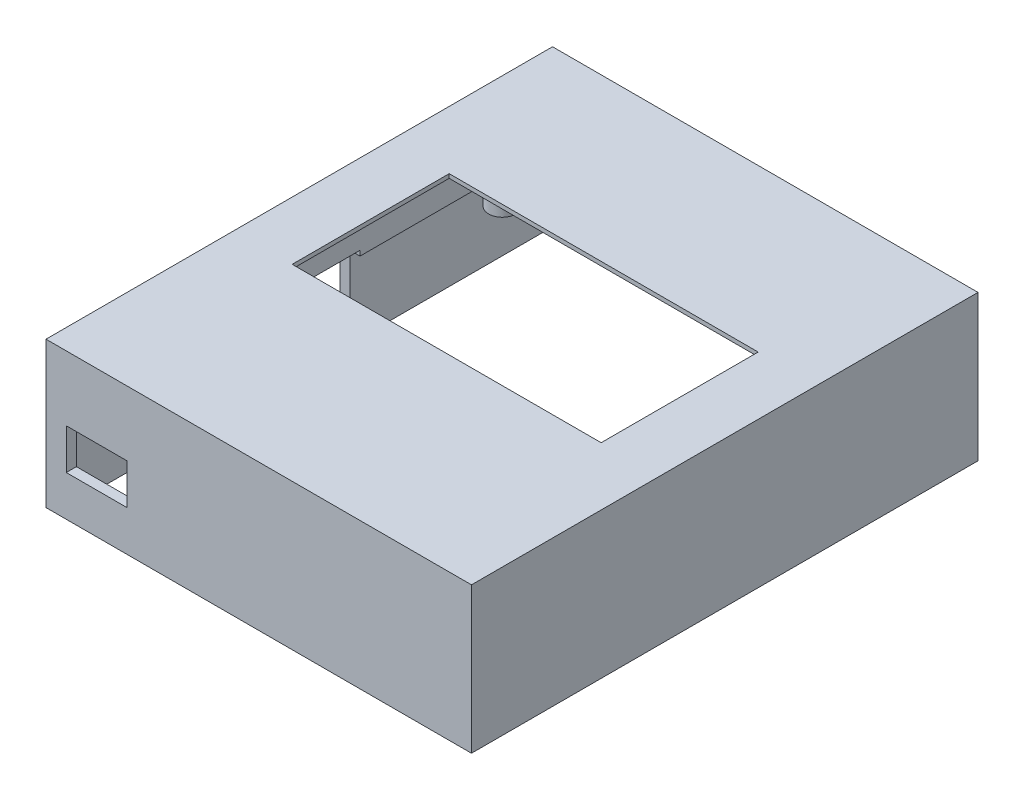
SolidWorks part; units mm, degrees
ref_plane "정면" through (0, 0, 0) normal (0, 0, 1) x (1, 0, 0)
ref_plane "윗면" through (0, 0, 0) normal (0, 1, 0) x (1, 0, 0)
ref_plane "우측면" through (0, 0, 0) normal (1, 0, 0) x (0, 0, -1)
sketch "스케치1" plane through (0, 0, 0) normal (0, 1, 0) x (1, 0, 0)
  line L1 (-21, 25) -> (21, 25)
  line L2 (-21, 25) -> (-21, -25)
  line L3 (-21, -25) -> (21, -25)
  line L4 (21, 25) -> (21, -25)
  line L5 (-21, 25) -> (21, -25) construction
  line L6 (-21, -25) -> (21, 25) construction
  point P0 (0, 0)
  dimension "D1" = 42
  dimension "D2" = 50
extrude "Body" add sketch "스케치1" along normal blind 0.4
sketch "스케치3" plane through (0, 0, 0) normal (0, -1, 0) x (1, 0, 0)
  line L1 (-15.25, 14.3) -> (15.25, 14.3) construction
  line L2 (-15.25, 14.3) -> (-15.25, -14.3) construction
  line L3 (-15.25, -14.3) -> (15.25, -14.3) construction
  line L4 (15.25, 14.3) -> (15.25, -14.3) construction
  line L5 (-15.25, 14.3) -> (15.25, -14.3) construction
  line L6 (-15.25, -14.3) -> (15.25, 14.3) construction
  circle A1 centre (15.25, 14.3) radius 1.35
  circle A3 centre (-15.25, -14.3) radius 1.35
  point P0 (0, 0)
  point P5 (0, 0)
  dimension "D4" = 2.7
  dimension "D1" = 30.5
  dimension "D2" = 28.6
extrude "OLED_pillar" add sketch "스케치3" along normal blind 5
sketch "스케치2" plane through (0, 0.4, 0) normal (0, 1, 0) x (1, 0, 0)
  line L1 (-15.25, 9.05) -> (15.25, 9.05)
  line L2 (-15.25, 9.05) -> (-15.25, -6.45)
  line L3 (-15.25, -6.45) -> (15.25, -6.45)
  line L4 (15.25, 9.05) -> (15.25, -6.45)
  line L5 (-15.25, 9.05) -> (15.25, -6.45) construction
  line L6 (-15.25, -6.45) -> (15.25, 9.05) construction
  point P0 (0, 0)
  point P5 (0, 1.3)
  dimension "D1" = 30.5
  dimension "D2" = 15.5
  dimension "D3" = 1.3
extrude "OLED_window" cut sketch "스케치2" against normal up to next
sketch "스케치4" plane through (0, 0, 0) normal (0, -1, 0) x (1, 0, 0)
  line L0 (20, 24) -> (-20, 24)
  line L5 (-20, 24) -> (-20, -24)
  line L6 (-20, -24) -> (20, -24)
  line L7 (20, -24) -> (20, 24)
  line L10 (21, -25) -> (21, 25)
  line L11 (21, 25) -> (-21, 25)
  line L12 (-21, 25) -> (-21, -25)
  line L13 (-21, -25) -> (21, -25)
  line L14 (21, -25) -> (21, 25)
  line L15 (21, 25) -> (-21, 25)
  line L16 (-21, 25) -> (-21, -25)
  line L17 (-21, -25) -> (21, -25)
  point P0 (0, 0)
  dimension "D1" = 0
  dimension "D2" = 1
extrude "FarmFeelWall" add sketch "스케치4" along normal blind 14
sketch "스케치5" plane through (0, 0, 0) normal (0, -1, 0) x (1, 0, 0)
  line L0 (-20, 24) -> (-20, -24) construction
  line L1 (-20, 18.1) -> (-19, 18.1)
  line L2 (-20, 18.1) -> (-20, -24)
  line L3 (-20, -24) -> (-19, -24)
  line L4 (-19, 18.1) -> (-19, -24)
  line L5 (-20, -24) -> (20, -24) construction
  line L7 (20, 24) -> (19, 24)
  line L8 (20, 24) -> (20, -24)
  line L9 (20, -24) -> (19, -24)
  line L10 (19, 24) -> (19, -24)
  dimension "D1" = 1
  dimension "D2" = 1
extrude "EspSupport" add sketch "스케치5" along normal blind 6
sketch "스케치7" plane through (-21, 0, 0) normal (-1, 0, 0) x (0, 0, 1)
  line L1 (9, -11.5) -> (-4, -11.5)
  line L2 (9, -11.5) -> (9, -5.5)
  line L3 (9, -5.5) -> (-4, -5.5)
  line L4 (-4, -11.5) -> (-4, -5.5)
  line L5 (9, -11.5) -> (-4, -5.5) construction
  line L6 (9, -5.5) -> (-4, -11.5) construction
  point P0 (2.5, -8.5)
  dimension "D1" = 2.5
  dimension "D2" = 8.5
  dimension "D3" = 13
  dimension "D4" = 6
extrude "micro5pin_window" cut sketch "스케치7" against normal up to next
sketch "스케치9" plane through (0, 0, 25) normal (0, 0, 1) x (1, 0, 0)
  line L1 (-13, -10) -> (-19, -10)
  line L2 (-13, -10) -> (-13, -6)
  line L3 (-13, -6) -> (-19, -6)
  line L4 (-19, -10) -> (-19, -6)
  line L5 (-13, -10) -> (-19, -6) construction
  line L6 (-13, -6) -> (-19, -10) construction
  point P0 (-16, -8)
  dimension "D1" = 8
  dimension "D2" = 16
  dimension "D3" = 6
  dimension "D4" = 4
extrude "reset_window" cut sketch "스케치9" against normal up to next
